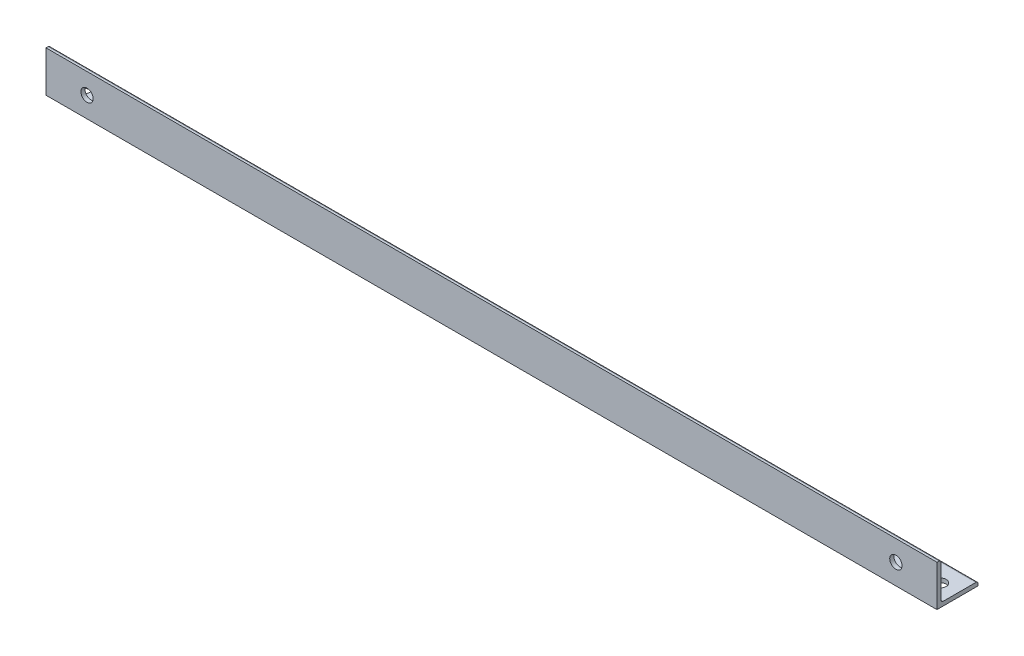
SolidWorks part; units mm, degrees
material "Простая углеродистая сталь"
ref_plane "Front" through (0, 0, 0) normal (0, 0, 1) x (1, 0, 0)
ref_plane "Top" through (0, 0, 0) normal (0, 1, 0) x (1, 0, 0)
ref_plane "Right" through (0, 0, 0) normal (1, 0, 0) x (0, 0, -1)
sketch "Эскиз1" plane through (0, 0, 0) normal (1, 0, 0) x (0, 0, -1)
  line L0 (0, 0) -> (0, 20)
  line L1 (0, 0) -> (20, 0)
  line L2 (0, 20) -> (1, 20)
  line L3 (2, 19) -> (2, 3)
  line L4 (3, 2) -> (19, 2)
  line L5 (20, 1) -> (20, 0)
  arc A0 (19, 2) -> (20, 1) centre (19, 1) cw
  arc A1 (1, 20) -> (2, 19) centre (1, 19) cw
  arc A2 (2, 3) -> (3, 2) centre (3, 3) ccw
  point P9 (20, 2)
  point P12 (2, 20)
  dimension "D5" = 1
  dimension "D1" = 20
  dimension "D2" = 20
  dimension "D3" = 2
  dimension "D4" = 2
extrude "Бобышка-Вытянуть1" add sketch "Эскиз1" along normal blind 434
sketch "Эскиз2" plane through (0, 0, 0) normal (0, -1, 0) x (1, 0, 0)
  line L0 (434, -20) -> (0, -20) construction
  line L1 (0, 0) -> (0, -20) construction
  line L2 (434, 0) -> (434, -20) construction
  circle A0 centre (425.5, -10) radius 3
  circle A1 centre (8.5, -10) radius 3
  dimension "D1" = 10
  dimension "D2" = 6
  dimension "D3" = 6
  dimension "D4" = 8.5
  dimension "D5" = 8.5
  dimension "D6" = 10
extrude "Вырез-Вытянуть1" cut sketch "Эскиз2" against normal through all
sketch "Эскиз3" plane through (0, 0, -2) normal (0, 0, -1) x (-1, 0, 0)
  line L0 (-434, 3) -> (-434, 19) construction
  line L1 (-434, 20) -> (0, 20) construction
  line L2 (0, 3) -> (0, 19) construction
  circle A0 centre (-414, 10) radius 3
  circle A1 centre (-20, 10) radius 3
  dimension "D1" = 6
  dimension "D2" = 20
  dimension "D3" = 10
  dimension "D4" = 6
  dimension "D5" = 10
  dimension "D6" = 20
extrude "Вырез-Вытянуть2" cut sketch "Эскиз3" against normal through all
sketch "Эскиз4" plane through (0, 0, 0) normal (0, -1, 0) x (1, 0, 0)
  line L0 (434, -20) -> (0, -20) construction
  circle A0 centre (400.5, -10) radius 2.5
  circle A1 centre (425.5, -10) radius 3 construction
  circle A2 centre (33.5, -10) radius 2.5
  circle A3 centre (8.5, -10) radius 3 construction
  dimension "D1" = 5
  dimension "D2" = 10
  dimension "D3" = 25
  dimension "D4" = 5
  dimension "D5" = 25
  dimension "D6" = 10
extrude "Вырез-Вытянуть3" [suppressed] cut sketch "Эскиз4" against normal blind 2
sketch "Эскиз5" plane through (0, 2, 0) normal (0, 1, 0) x (1, 0, 0)
  line L0 (434, 20) -> (0, 20) construction
  circle A0 centre (184.5, 10) radius 3
  circle A1 centre (425.5, 10) radius 3 construction
  dimension "D1" = 6
  dimension "D2" = 10
  dimension "D3" = 241
extrude "Вырез-Вытянуть4" cut sketch "Эскиз5" against normal blind 2
sketch "Эскиз6" plane through (0, 2, 0) normal (0, 1, 0) x (1, 0, 0)
  line L0 (434, 20) -> (0, 20) construction
  circle A0 centre (249.5, 10) radius 3
  circle A1 centre (8.5, 10) radius 3 construction
  dimension "D1" = 6
  dimension "D2" = 10
  dimension "D3" = 241
extrude "Вырез-Вытянуть5" [suppressed] cut sketch "Эскиз6" against normal blind 2
